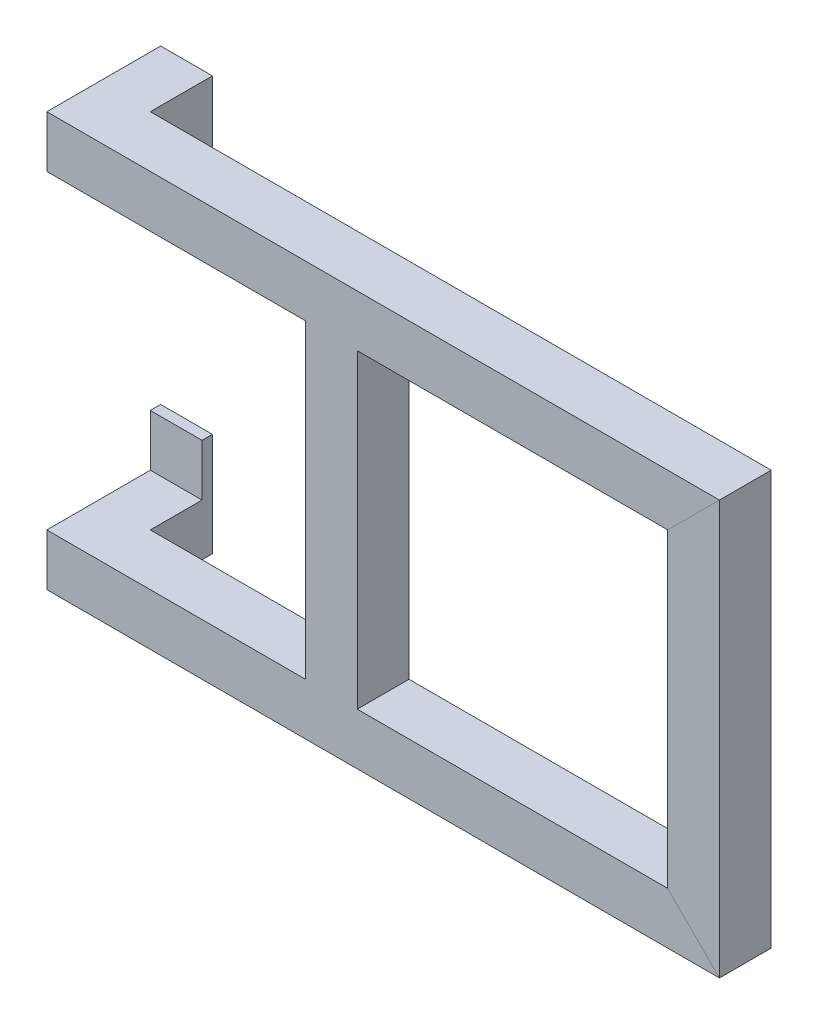
SolidWorks part; units mm, degrees
ref_plane "Front Plane" through (0, 0, 0) normal (0, 0, 1) x (1, 0, 0)
ref_plane "Top Plane" through (0, 0, 0) normal (0, 1, 0) x (1, 0, 0)
ref_plane "Right Plane" through (0, 0, 0) normal (1, 0, 0) x (0, 0, -1)
sketch "Sketch1" plane through (0, 0, 0) normal (0, 0, 1) x (1, 0, 0)
  line L1 (-325, 200) -> (325, 200)
  line L3 (-325, -200) -> (325, -200)
  line L4 (325, 200) -> (325, -200)
  line L5 (-325, 200) -> (325, -200) construction
  line L6 (-325, -200) -> (325, 200) construction
  point P0 (0, 0)
  dimension "D1" = 650
  dimension "D2" = 400
  dimension "D3" = 200
sketch "Sketch8" plane through (0, 0, 0) normal (1, 0, 0) x (0, 0, -1)
  line L1 (0, 200) -> (50, 200)
  line L2 (0, 200) -> (0, 150)
  line L3 (0, 150) -> (50, 150)
  line L4 (50, 200) -> (50, 150)
  line L5 (0, 200) -> (50, 150) construction
  line L6 (0, 150) -> (50, 200) construction
  point P0 (25, 175)
  dimension "D1" = 50
  dimension "D2" = 50
sweep "Sweep1" add profiles "Sketch8" path "Sketch1"
sketch "Sketch9" plane through (0, 0, 0) normal (0, 0, 1) x (1, 0, 0)
  line L0 (-325, 150) -> (275, 150) construction
  line L1 (-325, 200) -> (-275, 200)
  line L2 (-325, 200) -> (-325, 150)
  line L3 (-325, 150) -> (-275, 150)
  line L4 (-275, 200) -> (-275, 150)
  line L5 (325, -200) -> (-325, -200) construction
  line L6 (-325, -150) -> (-275, -150)
  line L7 (-325, -150) -> (-325, -200)
  line L8 (-325, -200) -> (-275, -200)
  line L9 (-275, -150) -> (-275, -200)
  dimension "D1" = 50
extrude "Boss-Extrude1" add sketch "Sketch9" against normal blind 110
sketch "Sketch10" plane through (0, 0, 0) normal (0, 0, 1) x (1, 0, 0)
  line L0 (-325, 200) -> (325, 200) construction
  line L1 (-75, 200) -> (-25, 200)
  line L2 (-75, 200) -> (-75, -200)
  line L3 (-75, -200) -> (-25, -200)
  line L4 (-25, 200) -> (-25, -200)
  line L5 (325, -200) -> (-325, -200) construction
  line L6 (325, 200) -> (325, -200) construction
  dimension "D1" = 50
  dimension "D2" = 400
extrude "Boss-Extrude2" add sketch "Sketch10" against normal blind 50
sketch "Sketch11" plane through (0, 0, -110) normal (0, 0, -1) x (-1, 0, 0)
  line L0 (325, 200) -> (325, 150) construction
  line L1 (275, 200) -> (325, 200)
  line L2 (275, 200) -> (275, 100)
  line L3 (275, 100) -> (325, 100)
  line L4 (325, 200) -> (325, 100)
  line L5 (275, -150) -> (275, -200) construction
  line L6 (325, -200) -> (275, -200)
  line L7 (325, -200) -> (325, -100)
  line L8 (325, -100) -> (275, -100)
  line L9 (275, -200) -> (275, -100)
  dimension "D1" = 100
  dimension "D2" = 100
extrude "Boss-Extrude3" add sketch "Sketch11" against normal blind 10
